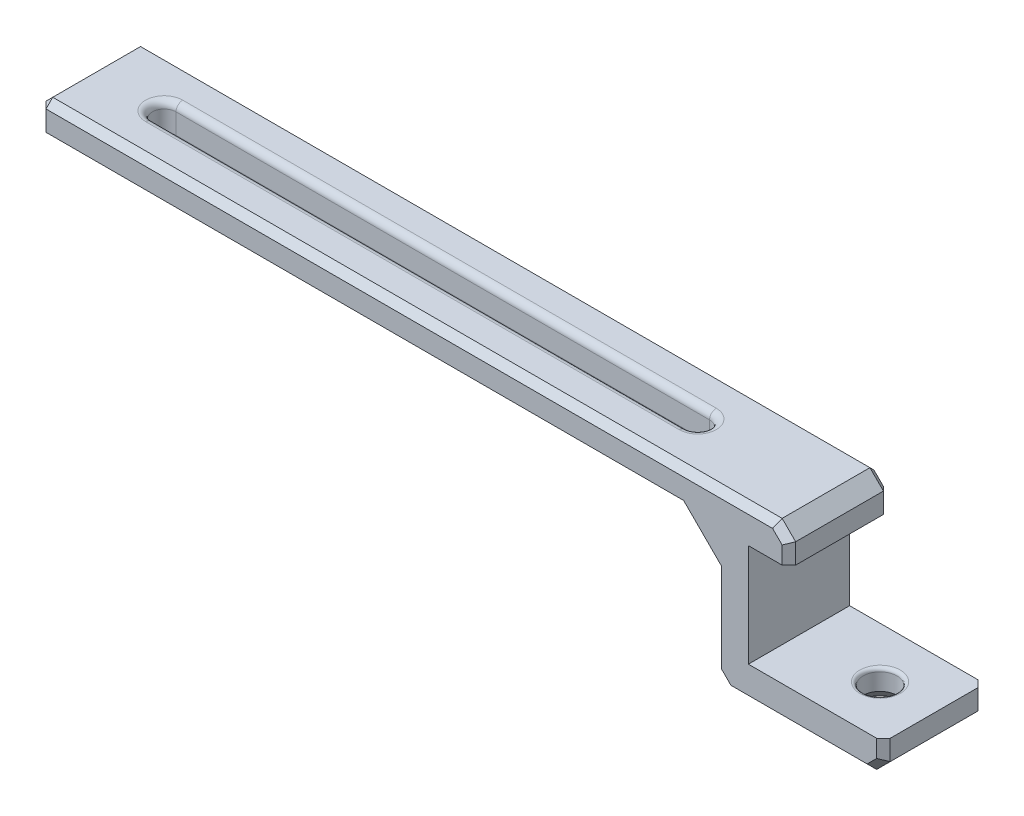
SolidWorks part; units mm, degrees
ref_plane "Plano frontal" through (0, 0, 0) normal (0, 0, 1) x (1, 0, 0)
ref_plane "Plano superior" through (0, 0, 0) normal (0, 1, 0) x (1, 0, 0)
ref_plane "Plano direito" through (0, 0, 0) normal (1, 0, 0) x (0, 0, -1)
sketch "Esboço1" plane through (0, 0, 0) normal (0, 0, 1) x (1, 0, 0)
  line L1 (0.2994, -0.75) -> (-5.7006, -0.75)
  line L3 (-5.7006, -15.95) -> (14.2994, -15.95)
  line L4 (14.2994, -15.95) -> (14.2994, -20.95)
  line L5 (14.2994, -20.95) -> (-10.7006, -20.95)
  line L7 (0.2994, 4.25) -> (0.2994, -0.75)
  line L9 (-5.7006, -0.75) -> (-5.7006, -15.95)
  line L15 (0.2994, 4.25) -> (-110.7006, 4.25)
  line L16 (-110.7006, 4.25) -> (-110.7006, -0.75)
  line L17 (-110.7006, -0.75) -> (-10.7006, -0.75)
  line L18 (-10.7006, -0.75) -> (-10.7006, -20.95)
  dimension "D1" = 5
  dimension "D2" = 20
  dimension "D3" = 15.2
  dimension "D4" = 6
  dimension "D5" = 5
  dimension "D6" = 100
  dimension "D7" = 5
  dimension "D8" = 5
extrude "Ressalto-extrusão1" add sketch "Esboço1" along normal blind 15
sketch "Esboço3" plane through (0, -20.95, 0) normal (0, -1, 0) x (1, 0, 0)
  line L0 (14.2994, 7.5) -> (6.2994, 7.5) construction
  line L1 (14.2994, 15) -> (14.2994, 0) construction
  circle A0 centre (6.2994, 7.5) radius 2.5
  dimension "D1" = 5
  dimension "D2" = 8
extrude "Corte-extrusão1" cut sketch "Esboço3" against normal blind 15
chamfer "Chanfro1" distance 2 angle 45 1 edges at (6.2994, -20.95, 5)
fillet "Filete1" radius 0.5 1 edges at (6.2994, -15.95, 5)
chamfer "Chanfro5" distance 2 angle 45 3 edges at (14.2994, -20.95, 7.5) (-10.7006, -20.95, 7.5) (0.2994, 4.25, 7.5)
chamfer "Chanfro7" distance 5 angle 45 1 edges at (-10.7006, -0.75, 7.5)
chamfer "Chanfro9" distance 1 angle 45 24 edges at (13.2994, -19.95, 0) (14.2994, -17.45, 0) (0.2994, 0.75, 0) (-0.7006, 3.25, 0) (-56.2006, 4.25, 0) (-110.7006, 1.75, 0) (-63.2006, -0.75, 0) (-13.2006, -3.25, 0) (-10.7006, -12.35, 0) (-9.7006, -19.95, 0) (1.7994, -20.95, 0) (-110.7006, 1.75, 15) (-56.2006, 4.25, 15) (-0.7006, 3.25, 15) (0.2994, 0.75, 15) (14.2994, -17.45, 15) (13.2994, -19.95, 15) (1.7994, -20.95, 15) (-9.7006, -19.95, 15) (-10.7006, -12.35, 15) (-13.2006, -3.25, 15) (-63.2006, -0.75, 15) (-110.7006, 4.25, 7.5) (-110.7006, -0.75, 7.5)
sketch "Esboço4" plane through (0, -0.75, 0) normal (0, -1, 0) x (1, 0, 0)
  line L0 (-109.7006, 7.5) -> (-15.7006, 7.5) construction
  line L1 (-109.7006, 14) -> (-109.7006, 1) construction
  line L2 (-15.7006, 1) -> (-15.7006, 14) construction
  line L3 (-99.7006, 7.5) -> (-20.7006, 7.5) construction
  line L4 (-99.7006, 9.25) -> (-20.7006, 9.25)
  line L5 (-99.7006, 5.75) -> (-20.7006, 5.75)
  arc A0 (-99.7006, 9.25) -> (-99.7006, 5.75) centre (-99.7006, 7.5) ccw
  arc A1 (-20.7006, 5.75) -> (-20.7006, 9.25) centre (-20.7006, 7.5) ccw
  point P8 (-60.2006, 7.5)
  dimension "D1" = 10
  dimension "D2" = 5
  dimension "D3" = 3.5
extrude "Corte-extrusão2" cut sketch "Esboço4" against normal blind 10
fillet "Filete2" radius 1 8 edges at (-101.4506, 4.25, 7.5) (-60.2006, 4.25, 9.25) (-18.9506, 4.25, 7.5) (-101.4506, -0.75, 7.5) (-60.2006, -0.75, 9.25) (-18.9506, -0.75, 7.5) (-60.2006, 4.25, 5.75) (-60.2006, -0.75, 5.75)
